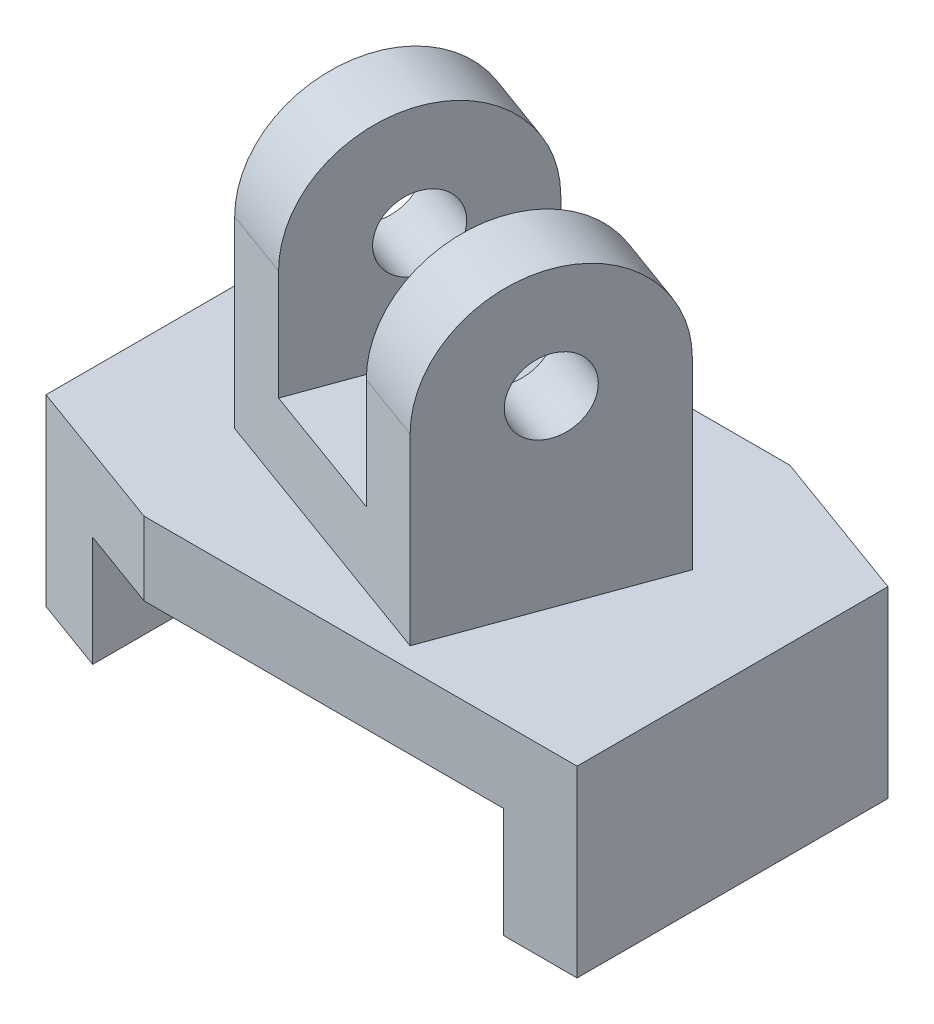
SolidWorks part; units mm, degrees
ref_plane "Спереди" through (0, 0, 0) normal (0, 0, 1) x (1, 0, 0)
ref_plane "Сверху" through (0, 0, 0) normal (0, 1, 0) x (1, 0, 0)
ref_plane "Справа" through (0, 0, 0) normal (1, 0, 0) x (0, 0, -1)
sketch "Эскиз1" plane through (0, 0, 0) normal (0, 1, 0) x (1, 0, 0)
  line L0 (0, -69.6927) -> (0, 93.9944) construction
  line L1 (-40, 25) -> (19, 25)
  line L2 (-40, 25) -> (-40, -17.3566)
  line L3 (-19, -25) -> (40, -25)
  line L4 (40, 17.3566) -> (40, -25)
  line L5 (-162.4302, 0) -> (167.4581, 0) construction
  line L6 (19, 25) -> (40, 17.3566)
  line L7 (-19, -25) -> (-40, -17.3566)
  dimension "D1" = 50
  dimension "D2" = 80
  dimension "D3" = 20
  dimension "D4" = 21
  dimension "D5" = 21
  dimension "D6" = 20
extrude "Бобышка-Вытянуть1" add sketch "Эскиз1" against normal blind 25
sketch "Эскиз2" plane through (0, 0, 25) normal (0, 0, 1) x (1, 0, 0)
  line L0 (-19, -25) -> (40, -25) construction
  line L1 (30, -25) -> (-30, -25)
  line L2 (30, -25) -> (30, -10)
  line L3 (30, -10) -> (-30, -10)
  line L4 (-30, -25) -> (-30, -10)
  line L5 (0, 20.4888) -> (0, -45.9149) construction
  line L7 (-19, 0) -> (40, 0) construction
  dimension "D1" = 60
  dimension "D2" = 10
extrude "Вырез-Вытянуть1" cut sketch "Эскиз2" against normal through all
sketch "Эскиз3" plane through (0, 0, 0) normal (0, 1, 0) x (1, 0, 0)
  line L1 (-12.9021, 19.7) -> (24.6856, 6.0192)
  line L2 (24.6856, 6.0192) -> (14.425, -22.1716)
  line L3 (14.425, -22.1716) -> (-23.1627, -8.4908)
  line L4 (-23.1627, -8.4908) -> (-12.9021, 19.7)
  line L5 (-19, -25) -> (40, -25) construction
  line L6 (19, 25) -> (-40, 25) construction
  line L7 (-40, -17.3566) -> (-19, -25) construction
  dimension "D1" = 25
  dimension "D2" = 40
  dimension "D3" = 70
  dimension "D4" = 5.3
  dimension "D5" = 30
extrude "Бобышка-Вытянуть2" add sketch "Эскиз3" along normal blind 40
sketch "Эскиз4" plane through (19.8634, 0, 7.2297) normal (0.9397, 0, 0.342) x (0.342, 0, -0.9397)
  line L0 (-29.0114, 25) -> (42.3036, 25) construction
  line L1 (-0.9008, 43.0082) -> (-0.9008, -7.3231) construction
  line L2 (-15.9008, 40) -> (-15.9008, 0) construction
  line L3 (-15.9008, 25) -> (-15.9008, 40)
  line L4 (-15.9008, 40) -> (-0.9008, 40)
  line L5 (-0.9008, 40) -> (14.0992, 40)
  line L6 (14.0992, 40) -> (14.0992, 25)
  circle A0 centre (-0.9008, 25) radius 5
  arc A1 (14.0992, 25) -> (-15.9008, 25) centre (-0.9008, 25) ccw
  line M8 (14.0992, 0) -> (14.0992, 40)
  line M9 (14.0992, 40) -> (-15.9008, 40)
  line M10 (-15.9008, 40) -> (-15.9008, 0)
  dimension "D3" = 10
  dimension "D4" = 15
  dimension "D1" = 25
  dimension "D2" = 15
  dimension "D5" = 15
extrude "Вырез-Вытянуть2" cut sketch "Эскиз4" against normal through all contours A1 M9 M10 | A1 M8 M9 | A0
sketch "Эскиз5" plane through (-5.4384, 0, 14.9419) normal (-0.342, 0, 0.9397) x (0.9397, 0, 0.342)
  line L0 (21.1382, 40) -> (-18.8618, 40) construction
  line L1 (-8.8618, 40) -> (11.1382, 40)
  line L2 (-8.8618, 40) -> (-8.8618, 10)
  line L3 (-8.8618, 10) -> (11.1382, 10)
  line L4 (11.1382, 40) -> (11.1382, 10)
  line L5 (21.1382, 25) -> (21.1382, 0) construction
  line L8 (-18.8618, 0) -> (21.1382, 0) construction
  dimension "D1" = 10
  dimension "D2" = 20
  dimension "D3" = 10
extrude "Вырез-Вытянуть3" cut sketch "Эскиз5" against normal blind 40
